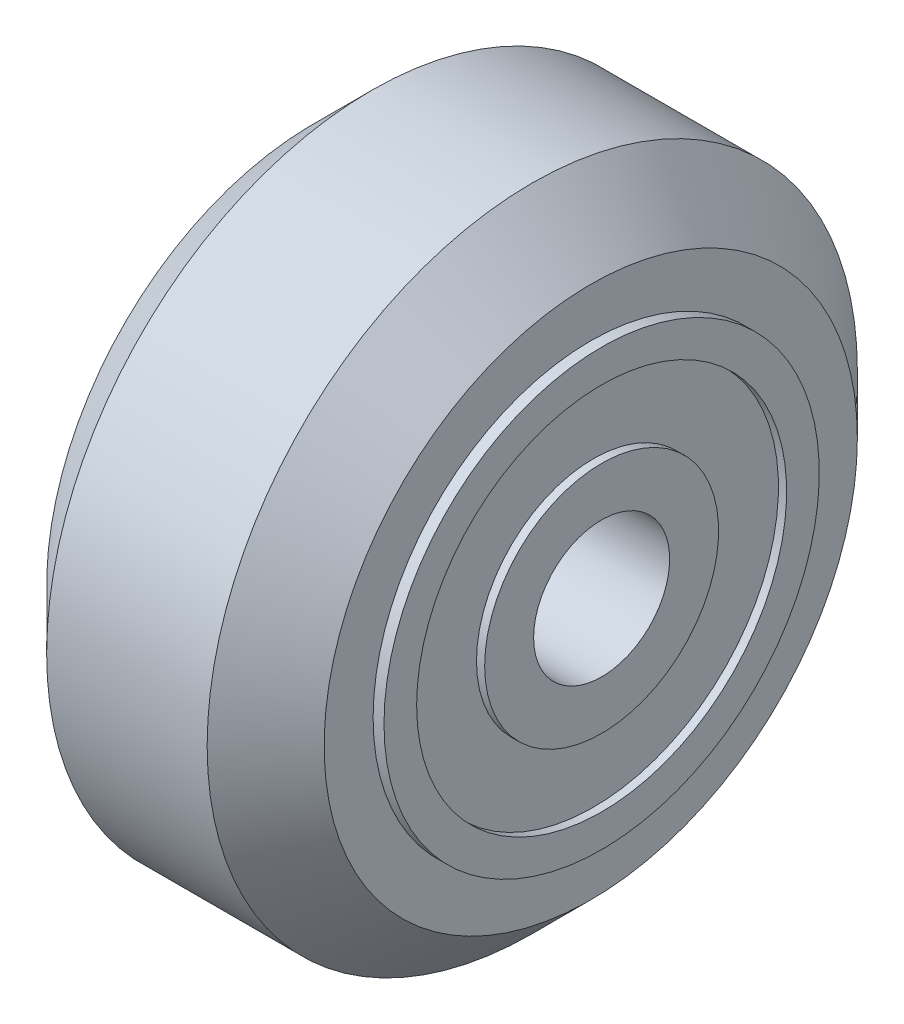
SolidWorks part; units mm, degrees
material "Delrin 2700 NC010, Low Viscosity Acetal Copolymer (SS)"
ref_plane "Front Plane" through (0, 0, 0) normal (0, 0, 1) x (1, 0, 0)
ref_plane "Top Plane" through (0, 0, 0) normal (0, 1, 0) x (1, 0, 0)
ref_plane "Right Plane" through (0, 0, 0) normal (1, 0, 0) x (0, 0, -1)
sketch "Sketch1" plane through (0, 0, 0) normal (0, 0, 1) x (1, 0, 0)
  line L0 (0.5, 7) -> (-0.5, 7)
  line L1 (-0.5, 7) -> (-0.5, 8)
  line L2 (-0.5, 8) -> (-5.1, 8)
  line L3 (-5.1, 8) -> (-5.1, 9.8)
  line L4 (-5.1, 9.8) -> (-2.95, 11.95)
  line L5 (-2.95, 11.95) -> (2.95, 11.95)
  line L6 (0, 11.95) -> (0, 7) construction
  line L7 (5.1, 9.8) -> (2.95, 11.95)
  line L8 (5.1, 8) -> (5.1, 9.8)
  line L9 (0.5, 8) -> (5.1, 8)
  line L10 (0.5, 7) -> (0.5, 8)
  line L11 (0, 0) -> (-12.6359, 0) construction
  dimension "D2" = 16
  dimension "D3" = 23.9
  dimension "D4" = 1
  dimension "D5" = 45
  dimension "D6" = 10.2
  dimension "D7" = 5.9
  dimension "D8" = 14
revolve "Revolve1" add sketch "Sketch1" angle 360 about L11
sketch "Esquisse1" plane through (-5.1, 0, 0) normal (-1, 0, 0) x (0, 0, 1)
  circle A0 centre (0, 0) radius 8
  circle A2 centre (0, 0) radius 2.5
  dimension "D1" = 16
  dimension "D2" = 5
extrude "Boss.-Extru.1" add sketch "Esquisse1" along normal blind 0.4 and the other way blind 10.6
sketch "Esquisse2" plane through (-5.5, 0, 0) normal (-1, 0, 0) x (0, 0, 1)
  circle A0 centre (0, 0) radius 6.8
  circle A1 centre (0, 0) radius 4.3
  dimension "D1" = 13.6
  dimension "D2" = 8.6
extrude "Enlèv. mat.-Extru.1" cut sketch "Esquisse2" against normal blind 0.3
mirror "Symétrie1" about plane through (0, 0, 0) normal (1, 0, 0) of "Enlèv. mat.-Extru.1"
